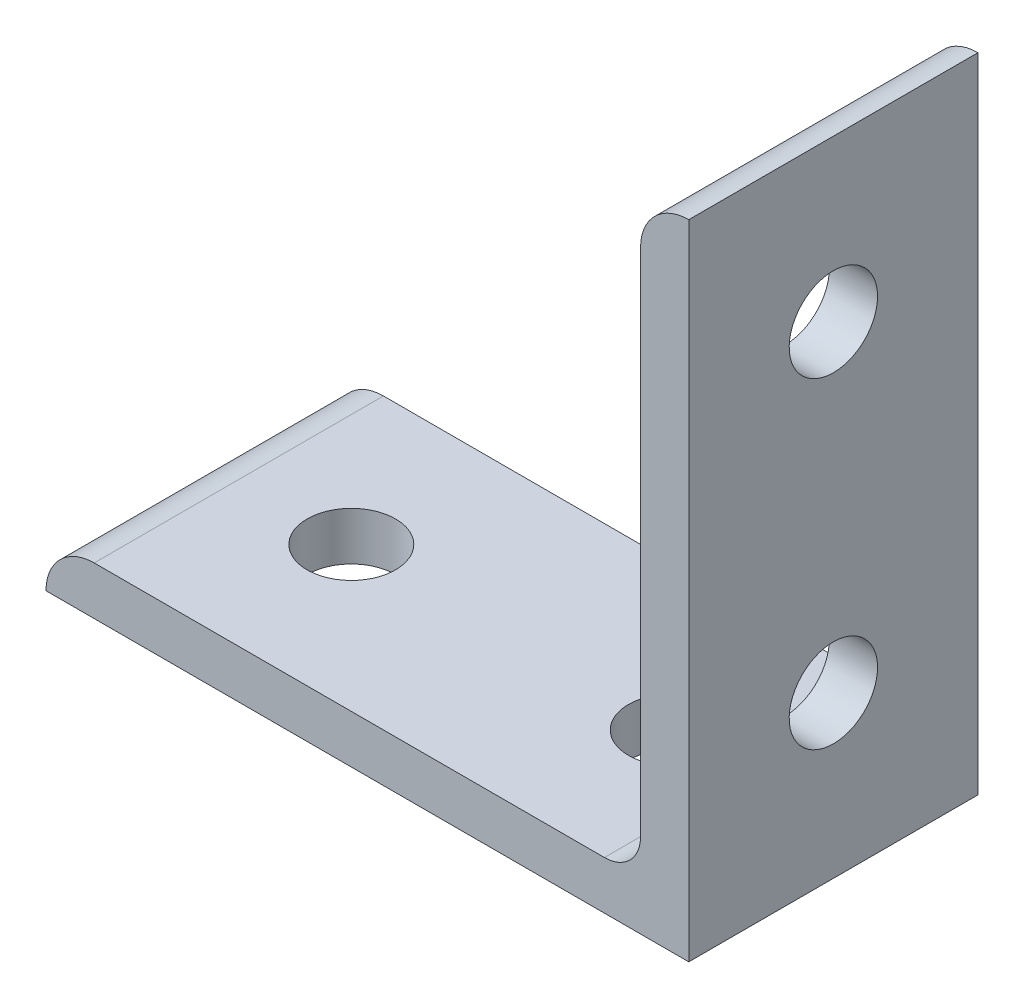
SolidWorks part; units mm, degrees
ref_plane "Front Plane" through (0, 0, 0) normal (0, 0, 1) x (1, 0, 0)
ref_plane "Top Plane" through (0, 0, 0) normal (0, 1, 0) x (1, 0, 0)
ref_plane "Right Plane" through (0, 0, 0) normal (1, 0, 0) x (0, 0, -1)
sketch "Sketch1" plane through (0, 0, 0) normal (0, 0, 1) x (1, 0, 0)
  line L0 (0, 0) -> (0, 40)
  line L1 (0, 0) -> (-40, 0)
  line L2 (-37, 3) -> (-5.25, 3)
  line L3 (-3, 5.25) -> (-3, 37)
  arc A0 (-40, 0) -> (-37, 3) centre (-37, 0) cw
  arc A1 (-3, 37) -> (0, 40) centre (0, 37) cw
  arc A2 (-5.25, 3) -> (-3, 5.25) centre (-5.25, 5.25) ccw
  point P11 (-21.125, 3)
  point P12 (-3, 21.125)
  dimension "D1" = 3
  dimension "D3" = 2.25
  dimension "D" = 3
  dimension "D2" = 3
  dimension "B" = 40
  dimension "C" = 40
extrude "Extrude1" add sketch "Sketch1" against normal mid plane 18
sketch "Sketch2" [suppressed] plane through (0, 6, 0) normal (0, 1, 0) x (1, 0, 0)
  circle A0 centre (-22.5, 0) radius 4.5
  dimension "hole" = 5.5
  dimension "hole height" = 10
extrude "Cut-Extrude1" [suppressed] cut sketch "Sketch2" against normal through all
sketch "Sketch3" [suppressed] plane through (-6, 0, 0) normal (-1, 0, 0) x (0, 0, 1)
  circle A0 centre (0, 22.5) radius 4.5
  dimension "D1" = 5.5
  dimension "D2" = 10
extrude "Cut-Extrude2" [suppressed] cut sketch "Sketch3" against normal through all
sketch "Sketch4" plane through (0, 3, 0) normal (0, 1, 0) x (1, 0, 0)
  line L0 (-37, 0) -> (-21.125, 0) construction
  line L1 (-21.125, 0) -> (-5.25, 0) construction
  circle A0 centre (-10, 0) radius 2.75
  circle A1 centre (-30, 0) radius 2.75
  dimension "D1" = 5.5
  dimension "D2" = 10
  dimension "D3" = 20
extrude "Cut-Extrude3" cut sketch "Sketch4" against normal through all
sketch "Sketch5" plane through (-3, 0, 0) normal (-1, 0, 0) x (0, 0, 1)
  circle A0 centre (0, 30) radius 2.75
  circle A1 centre (0, 10) radius 2.75
  dimension "D1" = 5.5
  dimension "D3" = 20
  dimension "D2" = 10
extrude "Cut-Extrude4" cut sketch "Sketch5" against normal through all
sketch "Sketch6" [suppressed] plane through (0, 3, 0) normal (0, 1, 0) x (1, 0, 0)
  line L0 (-10, 12.75) -> (-10, 19) construction
  line L1 (-5.25, -19) -> (-17, -19) construction
  line L2 (-10, -12.75) -> (-10, -19) construction
  line L3 (-5.25, 19) -> (-17, 19) construction
  circle A0 centre (-10, 10) radius 2.75
  circle A1 centre (-10, -10) radius 2.75
  dimension "D1" = 5.5
  dimension "D2" = 10
  dimension "distance" = 25.4
extrude "Cut-Extrude5" [suppressed] cut sketch "Sketch6" against normal through all
sketch "Sketch7" [suppressed] plane through (-3, 0, 0) normal (-1, 0, 0) x (0, 0, 1)
  line L0 (12.75, 10) -> (19, 10) construction
  line L2 (-12.75, 10) -> (-19, 10) construction
  line L4 (-19, 17) -> (-19, 5.25) construction
  line L5 (19, 17) -> (19, 5.25) construction
  circle A0 centre (-10, 10) radius 2.75
  circle A1 centre (10, 10) radius 2.75
  dimension "D2" = 5.5
  dimension "D1" = 25.4
  dimension "D3" = 10
extrude "Cut-Extrude6" [suppressed] cut sketch "Sketch7" against normal through all
sketch "Sketch8" [suppressed] plane through (0, 3, 0) normal (0, 1, 0) x (1, 0, 0)
  line L0 (-10, -10) -> (-10, -19) construction
  line L1 (-10, 10) -> (-10, 19) construction
  line L2 (-5.25, 19) -> (-37, 19) construction
  line L3 (-5.25, -19) -> (-37, -19) construction
  circle A0 centre (-30, -10) radius 2.75
  circle A1 centre (-10, -10) radius 2.75
  circle A2 centre (-10, 10) radius 2.75
  circle A3 centre (-30, 10) radius 2.75
  dimension "D1" = 5.5
  dimension "distance" = 25.4
  dimension "D2" = 10
  dimension "D3" = 20
extrude "Cut-Extrude7" [suppressed] cut sketch "Sketch8" against normal through all
sketch "Sketch9" [suppressed] plane through (-3, 0, 0) normal (-1, 0, 0) x (0, 0, 1)
  line L0 (10, 10) -> (19, 10) construction
  line L1 (-10, 10) -> (-19, 10) construction
  line L2 (-19, 37) -> (-19, 5.25) construction
  line L3 (19, 37) -> (19, 5.25) construction
  circle A0 centre (10, 10) radius 2.75
  circle A1 centre (10, 30) radius 2.75
  circle A2 centre (-10, 10) radius 2.75
  circle A3 centre (-10, 30) radius 2.75
  dimension "D1" = 5.5
  dimension "D2" = 25.4
  dimension "D3" = 10
  dimension "D4" = 20
extrude "Cut-Extrude8" [suppressed] cut sketch "Sketch9" against normal through all
equation "\"D2@Sketch1\" = \"D@Sketch1\""
equation "\"D3@Sketch1\" = \"D1@Sketch1\"*.750"
equation "\"D1@Sketch3\" = \"hole@Sketch2\""
equation "\"D1@Sketch4\" = \"hole@Sketch2\""
equation "\"D1@Sketch5\" = \"hole@Sketch2\""
equation "\"D1@Sketch6\" = \"hole@Sketch2\""
equation "\"D2@Sketch7\" = \"hole@Sketch2\""
equation "\"D1@Sketch7\" = \"distance@Sketch6\""
equation "\"D1@Sketch8\" = \"hole@Sketch2\""
equation "\"D1@Sketch9\" = \"hole@Sketch2\""
equation "\"D2@Sketch9\" = \"distance@Sketch8\""
equation "\"D2@Sketch3\" = \"hole height@Sketch2\""
equation "\"D2@Sketch6\" = \"hole height@Sketch2\""
equation "\"D3@Sketch7\" = \"hole height@Sketch2\""
equation "\"D2@Sketch4\" = \"hole height@Sketch2\""
equation "\"D3@Sketch4\" = \"hole height@Sketch2\"*2"
equation "\"D2@Sketch5\" = \"hole height@Sketch2\""
equation "\"D3@Sketch5\" = \"hole height@Sketch2\"*2"
equation "\"D2@Sketch8\" = \"hole height@Sketch2\""
equation "\"D3@Sketch8\" = \"hole height@Sketch2\"*2"
equation "\"D3@Sketch9\" = \"hole height@Sketch2\""
equation "\"D4@Sketch9\" = \"hole height@Sketch2\"*2"
